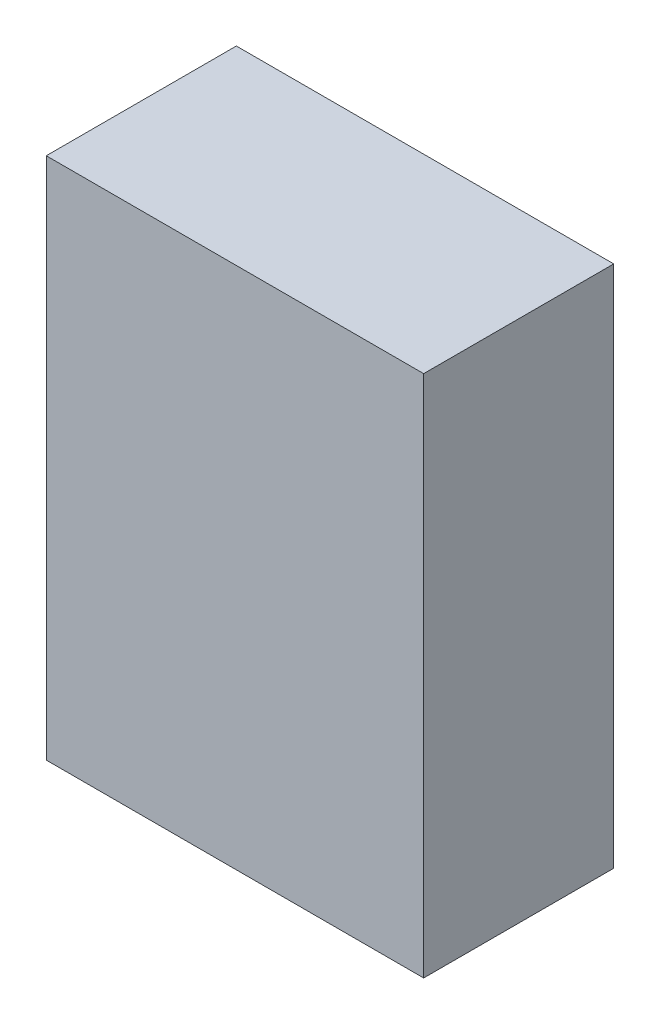
SolidWorks part; units mm, degrees
material "3.0205 (EN-AW 1200)"
ref_plane "Front Plane" through (0, 0, 0) normal (0, 0, 1) x (1, 0, 0)
ref_plane "Top Plane" through (0, 0, 0) normal (0, 1, 0) x (1, 0, 0)
ref_plane "Right Plane" through (0, 0, 0) normal (1, 0, 0) x (0, 0, -1)
sketch "AnchorSketch" plane through (0, 0, 0) normal (0, 0, 1) x (1, 0, 0)
  line L1 (0, 0) -> (17.125, 0)
  line L2 (0, 0) -> (0, 23.75)
  line L3 (0, 23.75) -> (17.125, 23.75)
  line L4 (17.125, 0) -> (17.125, 23.75)
  dimension "D1" = 17.125
  dimension "D2" = 23.75
extrude "AnchorBoss" add sketch "AnchorSketch" along normal blind 8.625
